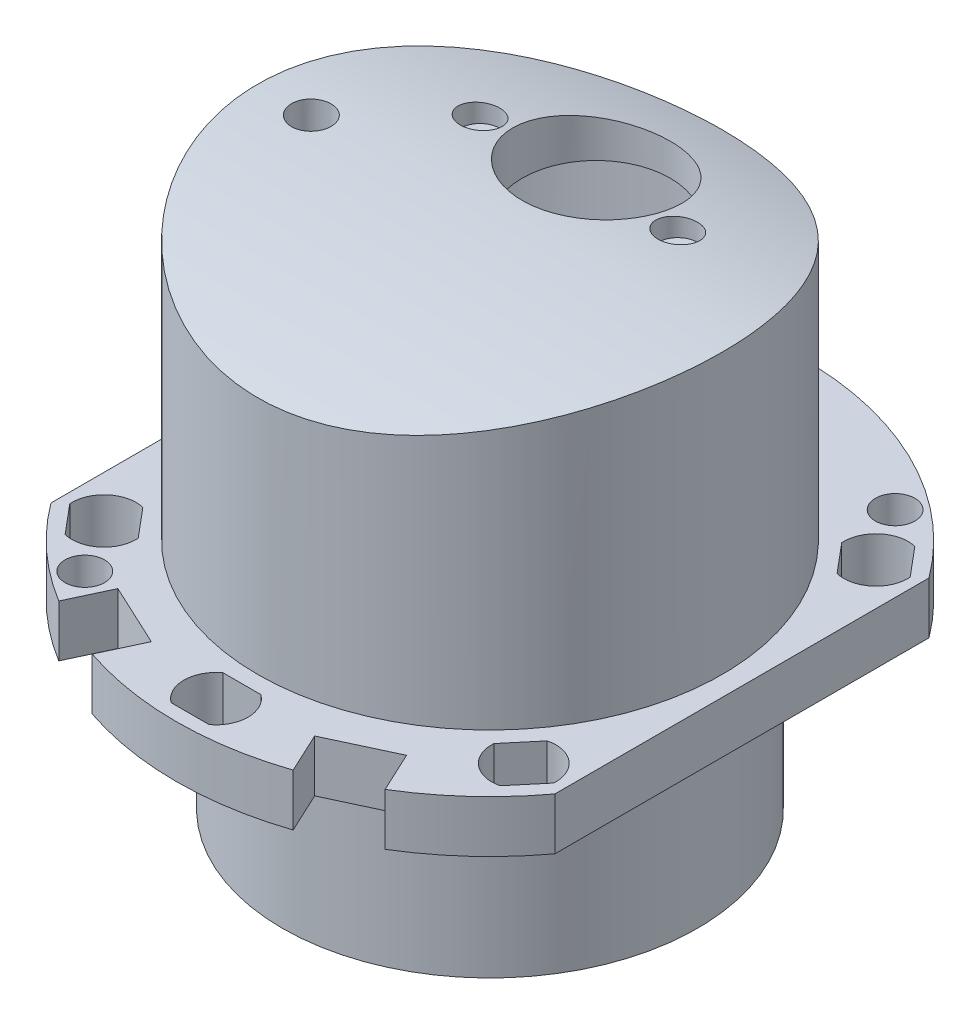
SolidWorks part; units mm, degrees
ref_plane "Front Plane" through (0, 0, 0) normal (0, 0, 1) x (1, 0, 0)
ref_plane "Top Plane" through (0, 0, 0) normal (0, 1, 0) x (1, 0, 0)
ref_plane "Right Plane" through (0, 0, 0) normal (1, 0, 0) x (0, 0, -1)
sketch "Sketch1" plane through (0, 0, 0) normal (0, 1, 0) x (1, 0, 0)
  line L0 (-51, 37.85) -> (-51, -37.85)
  line L21 (51, 37.85) -> (51, -37.85)
  arc A21 (-51, 37.85) -> (51, 37.85) centre (0, 0) cw
  arc A22 (-51, -37.85) -> (51, -37.85) centre (0, 0) ccw
  point P5 (-51, 0)
  dimension "D1" = 102
  dimension "D2" = 75.7
extrude "Boss-Extrude1" add sketch "Sketch1" against normal mid plane 10.5
sketch "Sketch2" plane through (0, 0, 0) normal (0, 1, 0) x (1, 0, 0)
  line L0 (-3.8324, 60.7) -> (3.8324, 60.7)
  line L1 (-3.8324, 50.2) -> (3.8324, 50.2)
  line L6 (0, 0) -> (0, 84.0469) construction
  line L7 (-51, 0) -> (51, 0) construction
  line L8 (-51, 37.85) -> (-51, -37.85) construction
  line L9 (51, -37.85) -> (51, 37.85) construction
  line L10 (0, 0) -> (63.8882, 53.6085) construction
  line L11 (0, 0) -> (-65.3028, 54.7955) construction
  line L12 (0, 0) -> (50.9975, 66.4612) construction
  line L13 (0, 0) -> (-96.4172, -80.9036) construction
  line L14 (0, 0) -> (-55.9099, -72.8631) construction
  line L15 (0, 0) -> (0, -81.8073) construction
  line L16 (0, 0) -> (76.6121, -64.2852) construction
  line L17 (0, 0) -> (-26.8408, 57.5603) construction
  line L18 (0, 0) -> (26.8408, 57.5603) construction
  line L19 (-35.992, 35.2037) -> (-40.9189, 29.3321)
  line L20 (-44.0355, 41.953) -> (-48.9623, 36.0814)
  line L21 (48.9623, 36.0814) -> (44.0355, 41.953)
  line L22 (40.9189, 29.3321) -> (35.992, 35.2037)
  line L23 (40.9189, -29.3321) -> (35.992, -35.2037)
  line L24 (48.9623, -36.0814) -> (44.0355, -41.953)
  line L25 (-3.8324, -50.2) -> (3.8324, -50.2)
  line L26 (-3.8324, -60.7) -> (3.8324, -60.7)
  line L27 (-35.992, -35.2037) -> (-40.9189, -29.3321)
  line L28 (-44.0355, -41.953) -> (-48.9623, -36.0814)
  line L29 (-51, 37.85) -> (51, -37.85) construction
  line L30 (26.8408, -57.5603) -> (0, 0) construction
  line L31 (-29.2179, -46.0946) -> (-33.0215, -54.2513)
  line L32 (-16.5296, -52.0112) -> (-29.2179, -46.0946)
  line L33 (20.3331, -60.168) -> (16.5296, -52.0112)
  line L34 (16.5296, -52.0112) -> (29.2179, -46.0946)
  line L35 (29.2179, -46.0946) -> (33.0215, -54.2513)
  line L36 (-20.3331, -60.168) -> (-16.5296, -52.0112)
  line L37 (-22.8737, -49.0529) -> (0, 0) construction
  arc A0 (-3.8324, 60.7) -> (-3.8324, 50.2) centre (0, 55.45) ccw
  arc A1 (3.8324, 50.2) -> (3.8324, 60.7) centre (0, 55.45) ccw
  circle A2 centre (0, 0) radius 55.45 construction
  circle A7 centre (35.604, 46.4) radius 4
  arc A8 (51, 37.85) -> (-51, 37.85) centre (0, 0) ccw construction
  arc A9 (-40.9189, 29.3321) -> (-48.9623, 36.0814) centre (-42.4772, 35.6426) cw
  arc A10 (-44.0355, 41.953) -> (-35.992, 35.2037) centre (-42.4772, 35.6426) cw
  arc A11 (48.9623, 36.0814) -> (40.9189, 29.3321) centre (42.4772, 35.6426) cw
  arc A12 (35.992, 35.2037) -> (44.0355, 41.953) centre (42.4772, 35.6426) cw
  arc A13 (48.9623, -36.0814) -> (40.9189, -29.3321) centre (42.4772, -35.6426) ccw
  arc A14 (35.992, -35.2037) -> (44.0355, -41.953) centre (42.4772, -35.6426) ccw
  arc A15 (3.8324, -50.2) -> (3.8324, -60.7) centre (0, -55.45) cw
  arc A16 (-3.8324, -60.7) -> (-3.8324, -50.2) centre (0, -55.45) cw
  arc A17 (-40.9189, -29.3321) -> (-48.9623, -36.0814) centre (-42.4772, -35.6426) ccw
  arc A18 (-44.0355, -41.953) -> (-35.992, -35.2037) centre (-42.4772, -35.6426) ccw
  arc A20 (-51, -37.85) -> (51, -37.85) centre (0, 0) ccw construction
  circle A21 centre (-35.604, -46.4) radius 4
  arc A22 (-33.0215, -54.2513) -> (-20.3331, -60.168) centre (0, 0) ccw
  arc A23 (20.3331, -60.168) -> (33.0215, -54.2513) centre (0, 0) ccw
  point P60 (22.8737, -49.0529)
  dimension "D3" = 6.5
  dimension "D4" = 50
  dimension "D7" = 12.5
  dimension "D8" = 8
  dimension "D18" = 8
  dimension "D1" = 60.7
  dimension "D2" = 10.5
  dimension "D5" = 37.5
  dimension "D6" = 50
  dimension "D9" = 46.4
  dimension "D10" = 37.5
  dimension "D11" = 12.5
  dimension "D12" = 25
  dimension "D13" = 25
  dimension "D14" = 14
  dimension "D15" = 9
  dimension "D16" = 14
  dimension "D17" = 25
  dimension "D19" = 46.4
extrude "Cut-Extrude1" cut sketch "Sketch2" against normal through all both and the other way through all
ref_plane "Plane1" through (0, 5.25, 0) normal (0, 1, 0) x (1, 0, 0)
sketch "Sketch3" plane through (0, 5.25, 0) normal (0, 1, 0) x (1, 0, 0)
  circle A0 centre (0, 0) radius 47
  dimension "D1" = 94
extrude "Boss-Extrude2" add sketch "Sketch3" along normal blind 56.5
sketch "Sketch4" plane through (0, 0, 0) normal (1, 0, 0) x (0, 0, -1)
  line L5 (-47, 53.7463) -> (-47, 76.5574)
  line L6 (-47, 76.5574) -> (47, 76.5574)
  line L7 (47, 76.5574) -> (47, 53.7463)
  line L11 (47, 5.25) -> (47, 61.75) construction
  line L12 (-47, 61.75) -> (-47, 5.25) construction
  line L13 (47, 61.75) -> (-47, 61.75) construction
  arc A5 (47, 53.7463) -> (-47, 53.7463) centre (0, -80.25) ccw
  point P1 (0, 76.5574)
  point P2 (0, 61.75)
  dimension "D1" = 142
  dimension "D2" = 22.8111
extrude "Cut-Extrude4" cut sketch "Sketch4" against normal through all both and the other way through all
sketch "Sketch5" plane through (0, 5.25, 0) normal (0, 1, 0) x (1, 0, 0)
  circle A5 centre (20, 18) radius 4
  circle A7 centre (-20, 18) radius 4
  circle A10 centre (0, 21.5) radius 15
  dimension "D2" = 30
  dimension "D3" = 8
  dimension "D4" = 8
  dimension "D6" = 18
  dimension "D9" = 21.5
  dimension "D10" = 20
  dimension "D11" = 20
extrude "Cut-Extrude5" cut sketch "Sketch5" along normal blind 56.5
ref_plane "Plane2" through (0, -5.25, 0) normal (0, -1, 0) x (-1, 0, 0)
sketch "Sketch6" plane through (0, -5.25, 0) normal (0, -1, 0) x (-1, 0, 0)
  circle A0 centre (0, 0) radius 42
  dimension "D1" = 84
extrude "Boss-Extrude3" add sketch "Sketch6" along normal blind 36.5
sketch "Sketch7" plane through (0, 0, 0) normal (0, 1, 0) x (1, 0, 0)
  circle A0 centre (0, 0) radius 39.5
  dimension "D1" = 79
extrude "Cut-Extrude6" cut sketch "Sketch7" against normal blind 42.5 and the other way blind 50.5
ref_plane "Plane4" through (0, 50.5, 0) normal (0, -1, 0) x (-1, 0, 0)
sketch "Sketch9" plane through (0, 50.5, 0) normal (0, -1, 0) x (-1, 0, 0)
  line L0 (0, 0) -> (0, 42) construction
  circle A0 centre (-20, 18) radius 4.8
  circle A1 centre (0, 0) radius 42 construction
  circle A2 centre (20, 18) radius 4.8
  dimension "D1" = 9.6
extrude "Boss-Extrude4" add sketch "Sketch9" against normal blind 6
sketch "Sketch10" plane through (0, 50.5, 0) normal (0, -1, 0) x (-1, 0, 0)
  line L0 (0, 0) -> (0, 42) construction
  circle A0 centre (-20, 18) radius 2.2
  circle A1 centre (20, 18) radius 2.2
  dimension "D1" = 4.4
extrude "Cut-Extrude7" cut sketch "Sketch10" against normal through all
sketch "Sketch11" plane through (0, 50.5, 0) normal (0, -1, 0) x (-1, 0, 0)
  line L0 (0, 0) -> (0, 39.5) construction
  circle A0 centre (-20, 18) radius 4.8
  circle A1 centre (0, 0) radius 39.5 construction
  circle A2 centre (20, 18) radius 4.8
  dimension "D1" = 9.6
extrude "Cut-Extrude8" cut sketch "Sketch11" against normal blind 4
ref_plane "Plane5" through (0, 61.75, 0) normal (0, 1, 0) x (1, 0, 0)
sketch "Sketch12" plane through (0, 61.75, 0) normal (0, 1, 0) x (1, 0, 0)
  circle A0 centre (-36.15, 0) radius 4
  circle A1 centre (-20, 18) radius 2.2 construction
  dimension "D1" = 8
  dimension "D2" = 36.15
  dimension "D3" = 18
extrude "Cut-Extrude9" cut sketch "Sketch12" against normal blind 11
sketch "Sketch13" plane through (0, 61.75, 0) normal (0, 1, 0) x (1, 0, 0)
  circle A0 centre (-36.15, 0) radius 3.5
  dimension "D1" = 7
extrude "Cut-Extrude10" cut sketch "Sketch13" against normal up to surface (11.25 mm away) up to face at (20, 50.5, -22.8)
